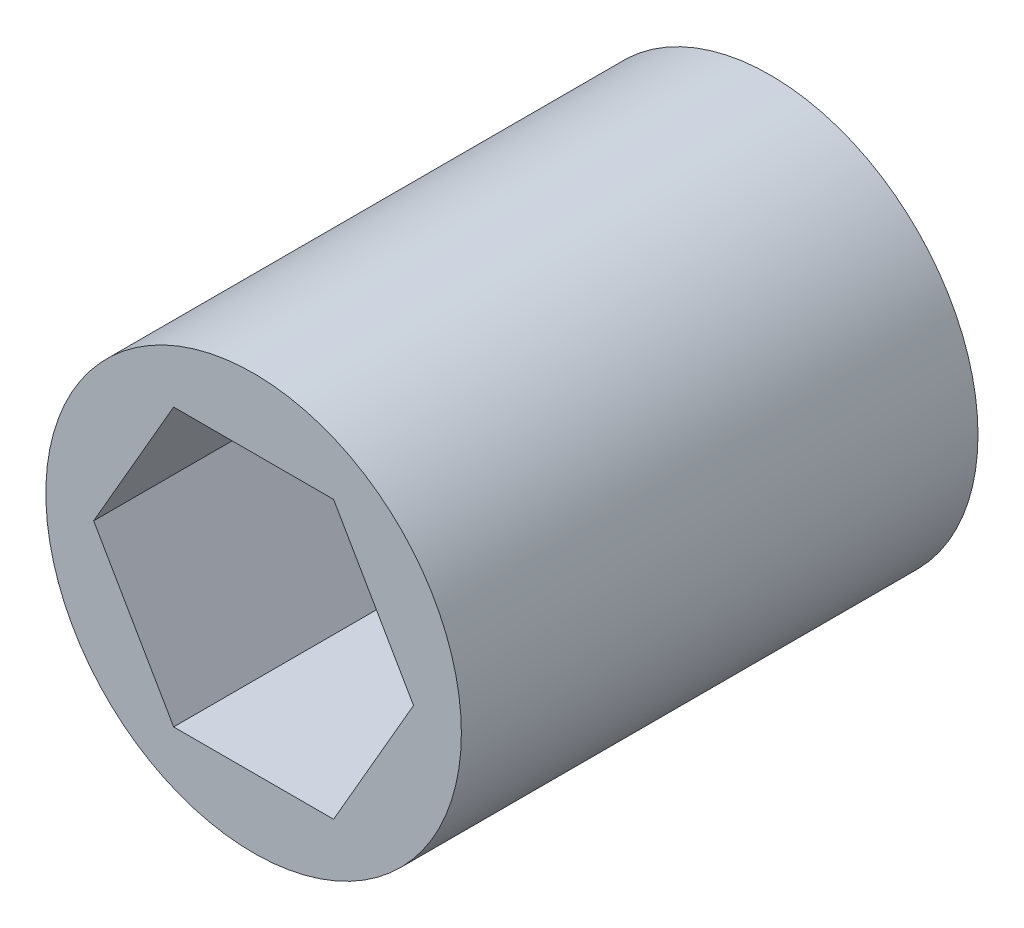
SolidWorks part; units mm, degrees
material "PET"
ref_plane "Front Plane" through (0, 0, 0) normal (0, 0, 1) x (1, 0, 0)
ref_plane "Top Plane" through (0, 0, 0) normal (0, 1, 0) x (1, 0, 0)
ref_plane "Right Plane" through (0, 0, 0) normal (1, 0, 0) x (0, 0, -1)
sketch "Sketch1" plane through (0, 0, 0) normal (0, 0, 1) x (1, 0, 0)
  line L1 (7.3323, 0) -> (3.6662, 6.35)
  line L2 (3.6662, 6.35) -> (-3.6662, 6.35)
  line L3 (-3.6662, 6.35) -> (-7.3323, 0)
  line L4 (-7.3323, 0) -> (-3.6662, -6.35)
  line L5 (-3.6662, -6.35) -> (3.6662, -6.35)
  line L6 (3.6662, -6.35) -> (7.3323, 0)
  circle A1 centre (0, 0) radius 6.35 construction
  circle A2 centre (0, 0) radius 9.525
  dimension "D1" = 12.7
  dimension "D2" = 19.05
extrude "Boss-Extrude1" add sketch "Sketch1" along normal blind 23.6855 contours L5 L6 L1 L2 L3 L4 | A2
